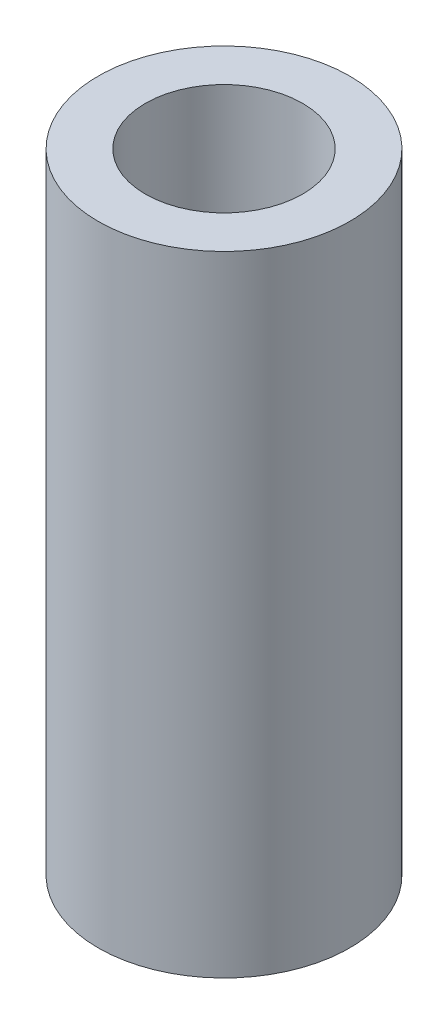
SolidWorks part; units mm, degrees
ref_plane "Front Plane" through (0, 0, 0) normal (0, 0, 1) x (1, 0, 0)
ref_plane "Top Plane" through (0, 0, 0) normal (0, 1, 0) x (1, 0, 0)
ref_plane "Right Plane" through (0, 0, 0) normal (1, 0, 0) x (0, 0, -1)
sketch "Sketch1" plane through (0, 0, 0) normal (0, 1, 0) x (1, 0, 0)
  circle A0 centre (0, 0) radius 2
  dimension "D1" = 4
extrude "Boss-Extrude1" add sketch "Sketch1" along normal blind 10
sketch "Sketch2" plane through (0, 0, 0) normal (0, -1, 0) x (1, 0, 0)
  circle A0 centre (0, 0) radius 1.25
  dimension "D1" = 2.5
extrude "Cut-Extrude1" cut sketch "Sketch2" against normal through all
